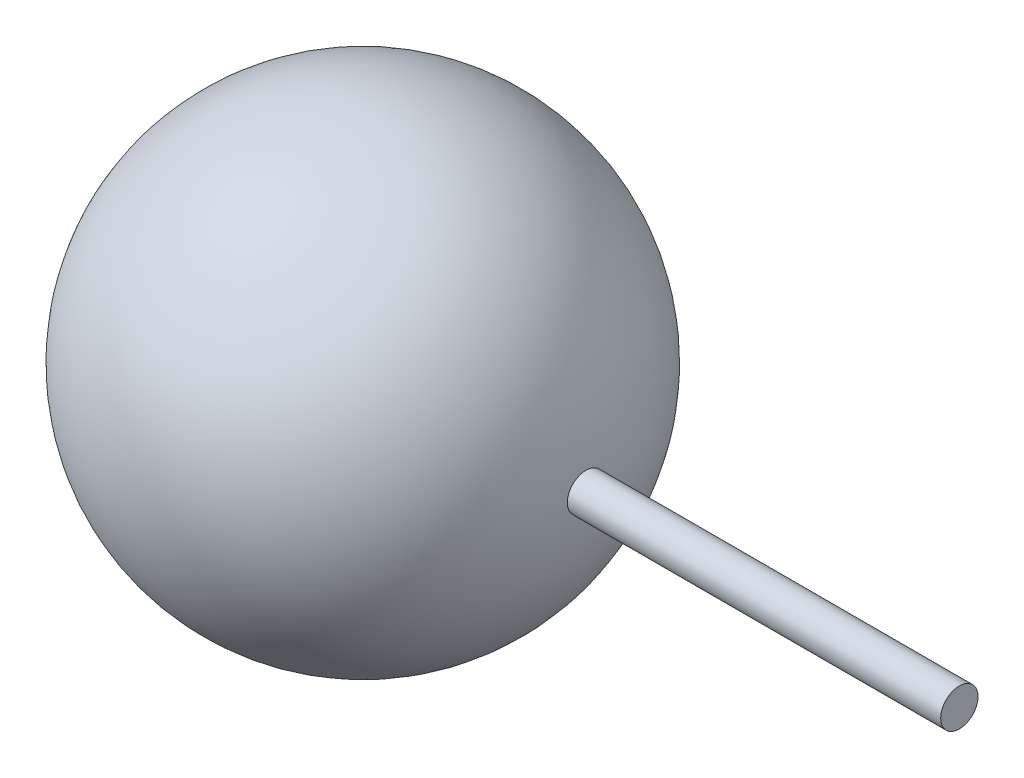
SolidWorks part; units mm, degrees
ref_plane "Front Plane" through (0, 0, 0) normal (0, 0, 1) x (1, 0, 0)
ref_plane "Top Plane" through (0, 0, 0) normal (0, 1, 0) x (1, 0, 0)
ref_plane "Right Plane" through (0, 0, 0) normal (1, 0, 0) x (0, 0, -1)
sketch "Sketch1" plane through (0, 0, 0) normal (0, 0, 1) x (1, 0, 0)
  line L0 (0, 0) -> (2655.807, 0) construction
  line L1 (2.9896, 0.25) -> (7.9896, 0.25)
  line L2 (7.9896, 0.25) -> (7.9896, 0)
  line L3 (7.9896, 0) -> (-3, 0)
  arc A0 (-3, 0) -> (2.9896, 0.25) centre (0, 0) cw
  dimension "D1" = 3
  dimension "D2" = 5
  dimension "D3" = 0.25
revolve "Revolve1" add sketch "Sketch1" angle 360 about L0
